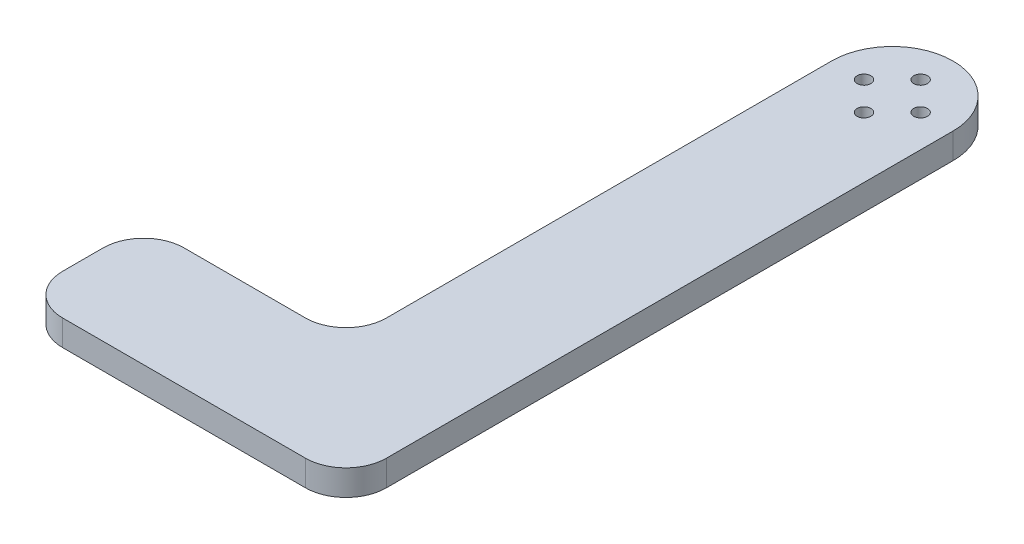
SolidWorks part; units mm, degrees
material "Pine"
ref_plane "Front Plane" through (0, 0, 0) normal (0, 0, 1) x (1, 0, 0)
ref_plane "Top Plane" through (0, 0, 0) normal (0, 1, 0) x (1, 0, 0)
ref_plane "Right Plane" through (0, 0, 0) normal (1, 0, 0) x (0, 0, -1)
sketch "Sketch2" plane through (0, 0, 0) normal (0, 1, 0) x (1, 0, 0)
  line L0 (-15, 0) -> (-15, -120)
  line L1 (-15, -120) -> (-65, -120)
  line L2 (-65, -120) -> (-65, -150)
  line L3 (-65, -150) -> (15, -150)
  line L4 (15, -150) -> (15, 0)
  circle A0 centre (0, 0) radius 15
  circle A1 centre (0, 0) radius 7 construction
  point P9 (15, -185.678)
  dimension "D1" = 30
  dimension "D2" = 14
  dimension "D3" = 30
  dimension "D4" = 50
  dimension "D5" = 150
extrude "Boss-Extrude1" add sketch "Sketch2" along normal blind 6.35 contours A0 L0 L1 L2 L3 L4 | A0
sketch "Sketch3" plane through (0, 6.35, 0) normal (0, 1, 0) x (1, 0, 0)
  circle A0 centre (0, 0) radius 7 construction
  circle A1 centre (0, 0) radius 7 construction
  point P3 (0, 7)
hole_wizard "M3 Clearance Hole1" positions "Sketch3" profile "Sketch4" hole size "M3" standard "ANSI Metric" end condition through all
sketch "Sketch4" plane through (0, 6.35, -7) normal (1, 0, 0) x (0, 0, 1)
  line L0 (0, 0) -> (0, 6.35)
  line L1 (0, 6.35) -> (1.7, 6.35)
  line L2 (1.7, 6.35) -> (1.7, 0)
  line L5 (1.7, 0) -> (0, 0)
  line L11 (0, -6.35) -> (0, 107.95) construction
  dimension "Thru Hole Dia." = 3.4
  dimension "Thru Hole Depth" = 6.35
pattern_circular "CirPattern1" count 4 over 360 about axis through (0, 0, 0) along (0, 1, 0) of "M3 Clearance Hole1"
fillet "Fillet1" radius 10 4 edges at (15, 3.175, 150) (-65, 3.175, 150) (-65, 3.175, 120) (-15, 3.175, 120)
